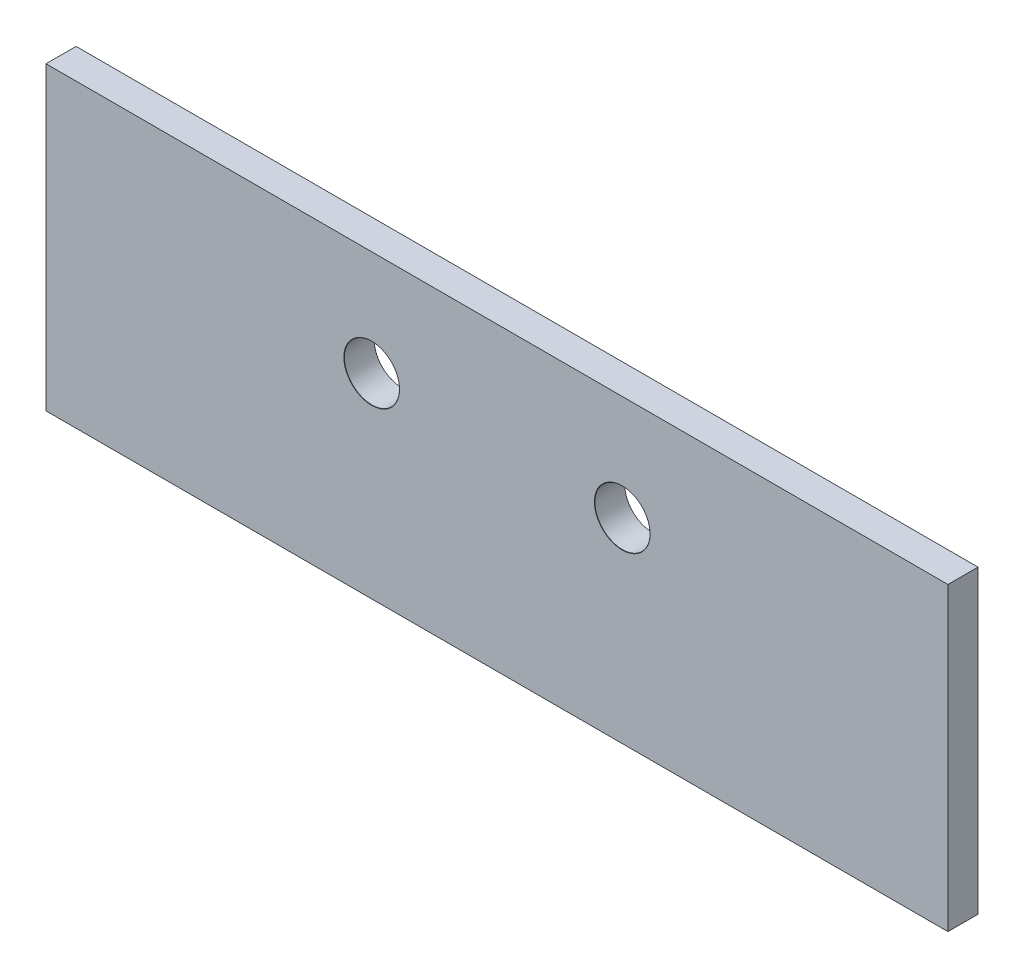
SolidWorks part; units mm, degrees
ref_plane "Front Plane" through (0, 0, 0) normal (0, 0, 1) x (1, 0, 0)
ref_plane "Top Plane" through (0, 0, 0) normal (0, 1, 0) x (1, 0, 0)
ref_plane "Right Plane" through (0, 0, 0) normal (1, 0, 0) x (0, 0, -1)
sketch "Sketch1" plane through (0, 0, 0) normal (0, 0, 1) x (1, 0, 0)
  line L1 (45, 15) -> (-45, 15)
  line L2 (45, 15) -> (45, -15)
  line L3 (45, -15) -> (-45, -15)
  line L4 (-45, 15) -> (-45, -15)
  line L5 (45, 15) -> (-45, -15) construction
  line L6 (45, -15) -> (-45, 15) construction
  point P0 (0, 0)
  dimension "D1" = 90
  dimension "D2" = 30
extrude "Boss-Extrude1" add sketch "Sketch1" along normal mid plane 3
sketch "Sketch2" plane through (0, 0, 1.5) normal (0, 0, 1) x (1, 0, 0)
  line L0 (0, 25.2707) -> (0, -32.0802) construction
  line L1 (-12.5, 4.5) -> (12.5, 4.5) construction
  line L3 (45, 15) -> (-45, 15) construction
  line L4 (-45, -3) -> (-15, -3) construction
  line L5 (-45, 15) -> (-45, -15) construction
  line L8 (-45, -15) -> (45, -15) construction
  line L9 (45, -3) -> (15, -3) construction
  point P3 (-12.5, 4.5)
  point P4 (12.5, 4.5)
  point P5 (0, 4.5)
  dimension "D1" = 25
  dimension "D2" = 10.5
  dimension "D3" = 30
  dimension "D4" = 12
hole_wizard "M5 Clearance Hole1" positions "Sketch2" profile "Sketch3" hole size "M5" standard "ISO" end condition through all
sketch "Sketch3" plane through (12.5, 4.5, 1.5) normal (1, 0, 0) x (0, -1, 0)
  line L0 (0, 0) -> (0, 3)
  line L1 (0, 3) -> (2.75, 3)
  line L2 (2.75, 3) -> (2.75, 0.025)
  line L3 (2.75, 0.025) -> (2.775, 0)
  line L5 (2.775, 0) -> (0, 0)
  line L6 (-2.75, 0.025) -> (-2.775, 0) construction
  line L11 (0, -6.35) -> (0, 107.95) construction
  dimension "Thru Hole Dia." = 5.5
  dimension "Thru Hole Depth" = 3
  dimension "Near C'Sink Dia." = 5.55
  dimension "Near C'Sink Angle" = 90
sketch "Sketch4" plane through (0, 0, 0) normal (0, 0, 1) x (1, 0, 0)
  line L1 (-45, -15) -> (-60, -15)
  line L2 (-45, -15) -> (-45, 15)
  line L3 (-45, 15) -> (-60, 15)
  line L4 (-60, -15) -> (-60, 15)
  line L5 (45, 15) -> (60, 15)
  line L6 (45, 15) -> (45, -15)
  line L7 (45, -15) -> (60, -15)
  line L8 (60, 15) -> (60, -15)
  dimension "D1" = 30
  dimension "D2" = 15
  dimension "D3" = 15
extrude "Boss-Extrude2" [suppressed] add sketch "Sketch4" along normal mid plane 3
